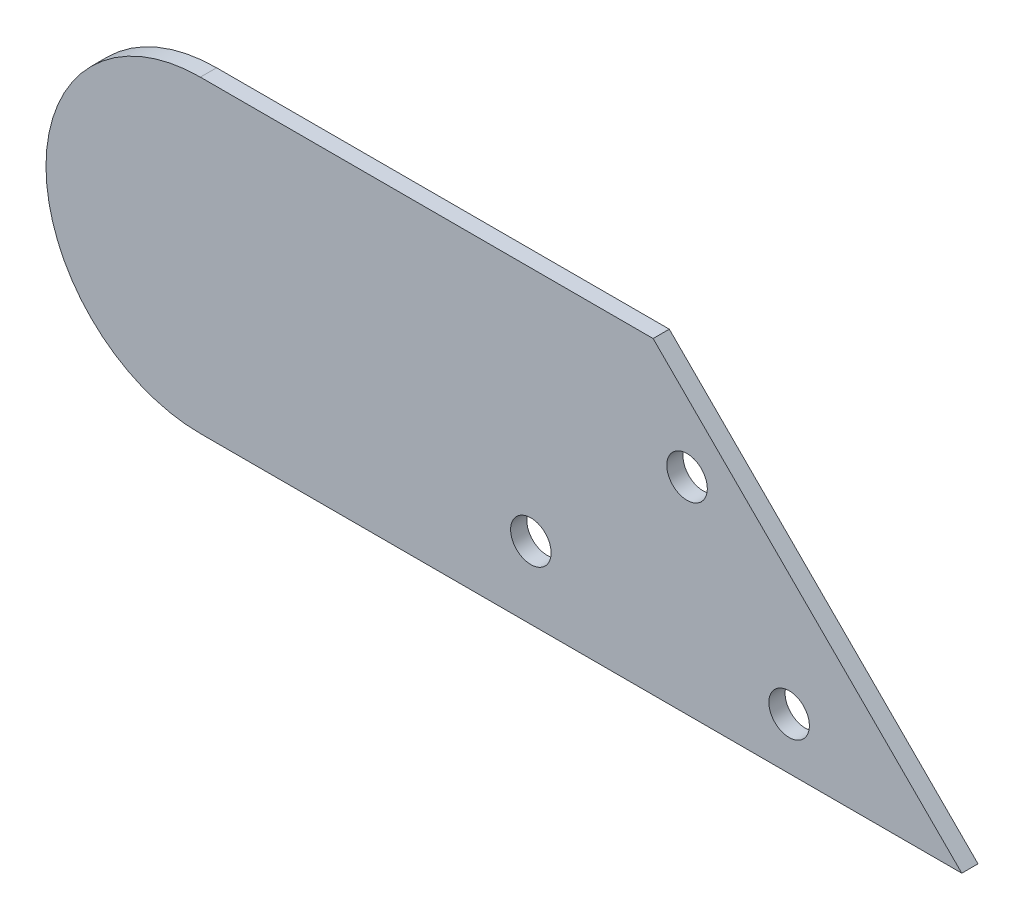
SolidWorks part; units mm, degrees
ref_plane "Front Plane" through (0, 0, 0) normal (0, 0, 1) x (1, 0, 0)
ref_plane "Top Plane" through (0, 0, 0) normal (0, 1, 0) x (1, 0, 0)
ref_plane "Right Plane" through (0, 0, 0) normal (1, 0, 0) x (0, 0, -1)
sketch "Sketch1" plane through (0, 0, 0) normal (0, 0, 1) x (1, 0, 0)
  line L0 (0, 0) -> (-38.1, 38.1)
  line L1 (-38.1, 38.1) -> (-93.98, 38.1)
  line L2 (-93.98, 38.1) -> (-93.98, 0) construction
  line L3 (-93.98, 0) -> (0, 0)
  arc A0 (-93.98, 38.1) -> (-93.98, 0) centre (-93.98, 19.05) ccw
  dimension "D1" = 45
  dimension "D2" = 93.98
  dimension "D3" = 38.1
extrude "Boss-Extrude1" add sketch "Sketch1" along normal blind 2 contours L1 A0 L3 L0
sketch "Sketch2" plane through (0, 0, 2) normal (0, 0, 1) x (1, 0, 0)
  line L0 (-93.98, 0) -> (0, 0) construction
  circle A0 centre (-53.1876, 8.89) radius 2.5
  circle A1 centre (-21.3118, 6.35) radius 2.5
  circle A2 centre (-33.909, 25.4) radius 2.5
  dimension "D1" = 5
  dimension "D2" = 5
  dimension "D3" = 5
  dimension "D4" = 6.35
  dimension "D5" = 22.2377
  dimension "D6" = 25.4
  dimension "D7" = 8.89
  dimension "D8" = 33.909
  dimension "D9" = 53.1876
extrude "Cut-Extrude1" cut sketch "Sketch2" against normal through all both and the other way through all
